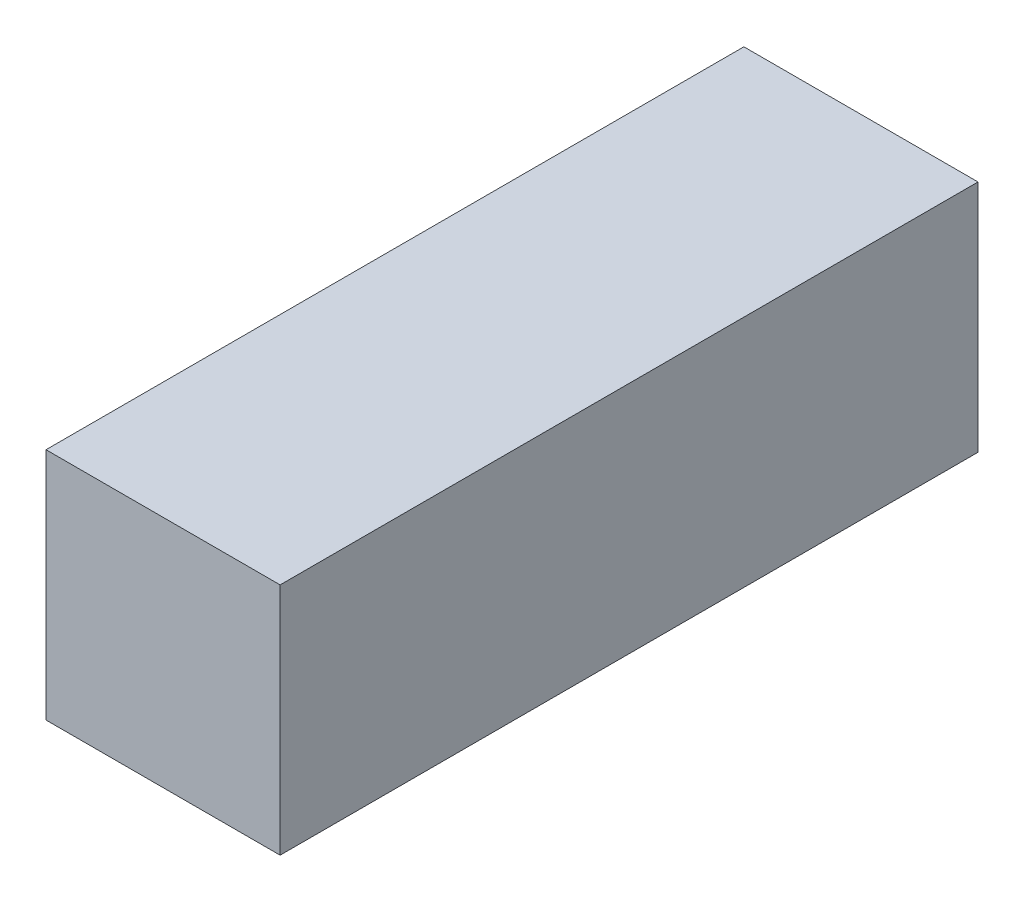
SolidWorks part; units mm, degrees
ref_plane "Front Plane" through (0, 0, 0) normal (0, 0, 1) x (1, 0, 0)
ref_plane "Top Plane" through (0, 0, 0) normal (0, 1, 0) x (1, 0, 0)
ref_plane "Right Plane" through (0, 0, 0) normal (1, 0, 0) x (0, 0, -1)
sketch "Sketch1" plane through (0, 0, 0) normal (0, 0, 1) x (1, 0, 0)
  line L0 (-1333.5, 2628.9) -> (-1333.5, -38.1)
  line L1 (-1295.4, 2590.8) -> (1295.4, 2590.8)
  line L2 (-1295.4, 2590.8) -> (-1295.4, 0)
  line L3 (-1295.4, 0) -> (1295.4, 0)
  line L4 (1295.4, 2590.8) -> (1295.4, 0)
  line L5 (-1295.4, 2590.8) -> (1295.4, 0) construction
  line L6 (-1295.4, 0) -> (1295.4, 2590.8) construction
  line L7 (-1333.5, -38.1) -> (1333.5, -38.1)
  line L8 (1333.5, 2628.9) -> (1333.5, -38.1)
  line L9 (-1333.5, 2628.9) -> (1333.5, 2628.9)
  point P0 (0, 1295.4)
  dimension "D1" = 2590.8
  dimension "D2" = 2590.8
  dimension "D3" = 38.1
extrude "Boss-Extrude1" add sketch "Sketch1" along normal blind 7924.8
sketch "Sketch2" plane through (0, 0, 7924.8) normal (0, 0, 1) x (1, 0, 0)
  line L0 (-1333.5, -38.1) -> (1333.5, -38.1) construction
  line L1 (1333.5, -38.1) -> (1333.5, 2628.9) construction
  line L2 (1333.5, 2628.9) -> (-1333.5, 2628.9) construction
  line L3 (-1333.5, 2628.9) -> (-1333.5, -38.1) construction
  line L4 (-1333.5, -38.1) -> (1333.5, -38.1)
  line L5 (1333.5, -38.1) -> (1333.5, 2628.9)
  line L6 (1333.5, 2628.9) -> (-1333.5, 2628.9)
  line L7 (-1333.5, 2628.9) -> (-1333.5, -38.1)
extrude "Boss-Extrude2" add sketch "Sketch2" along normal blind 25.4
sketch "Sketch3" plane through (0, 0, 7924.8) normal (0, 0, -1) x (-1, 0, 0)
  line L0 (0, 2590.8) -> (0, 0) construction
  line L1 (-1295.4, 2590.8) -> (1295.4, 2590.8) construction
